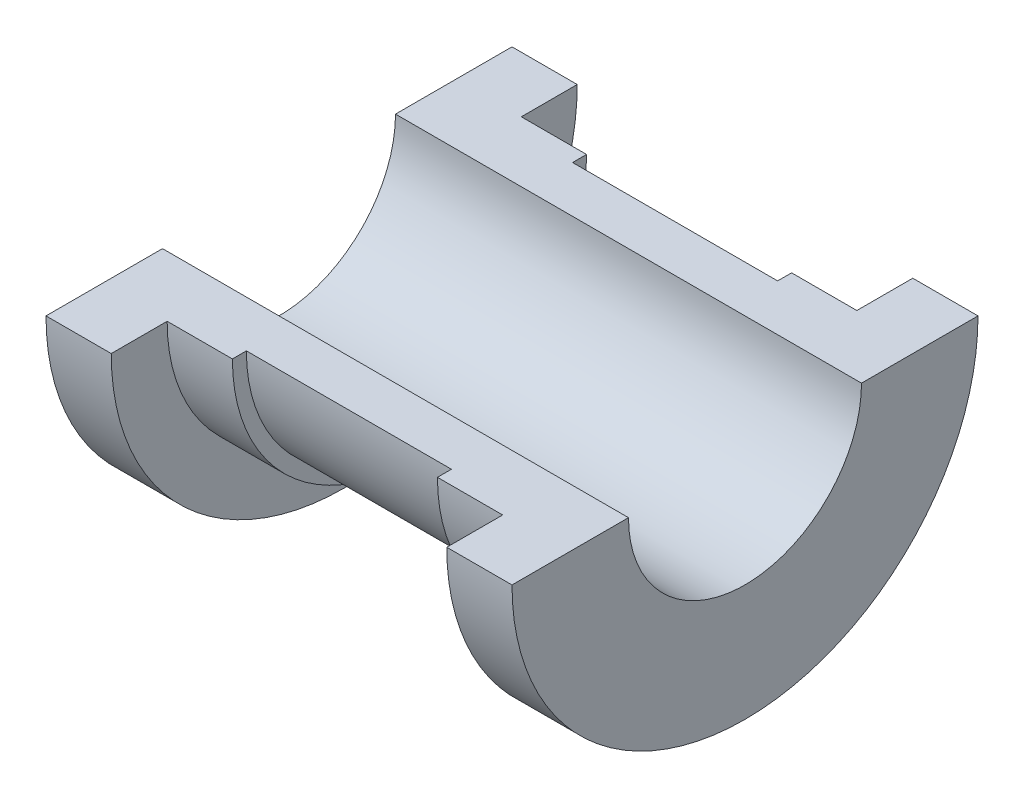
SolidWorks part; units mm, degrees
ref_plane "Front Plane" through (0, 0, 0) normal (0, 0, 1) x (1, 0, 0)
ref_plane "Top Plane" through (0, 0, 0) normal (0, 1, 0) x (1, 0, 0)
ref_plane "Right Plane" through (0, 0, 0) normal (1, 0, 0) x (0, 0, -1)
sketch "Sketch1" plane through (0, 0, 0) normal (0, 0, 1) x (1, 0, 0)
  line L0 (-25, 0) -> (25, 0)
  line L1 (25, 0) -> (25, 25)
  line L2 (25, 25) -> (18, 25)
  line L3 (18, 25) -> (18, 19)
  line L4 (18, 19) -> (11, 19)
  line L5 (11, 19) -> (11, 17.5)
  line L6 (11, 17.5) -> (-11, 17.5)
  line L8 (-11, 19) -> (-11, 17.5)
  line L9 (-18, 19) -> (-11, 19)
  line L10 (-18, 25) -> (-18, 19)
  line L11 (-25, 25) -> (-18, 25)
  line L12 (-25, 0) -> (-25, 25)
  dimension "D2" = 25
  dimension "D4" = 1.5
  dimension "D5" = 6
  dimension "D7" = 7
  dimension "D8" = 7
revolve "Revolve1" add sketch "Sketch1" angle 360 about L0
sketch "Sketch2" plane through (25, 0, 0) normal (1, 0, 0) x (0, 0, -1)
  circle A0 centre (0, 0) radius 12.5
extrude "Cut-Extrude1" cut sketch "Sketch2" against normal through all
sketch "Sketch3" plane through (25, 0, 0) normal (1, 0, 0) x (0, 0, -1)
  line L0 (-25, 0) -> (25, 0)
  circle A0 centre (0, 0) radius 25 construction
extrude "Cut-Extrude4" cut sketch "Sketch3" against normal through all and the other way through all
ref_plane "Plane2" through (0, -17.5, 0) normal (0, 1, 0) x (1, 0, 0)
sketch "Sketch5" plane through (0, -17.5, 0) normal (0, 1, 0) x (1, 0, 0)
  circle A0 centre (0, 0) radius 3
extrude "Boss-Extrude1" add sketch "Sketch5" along normal mid plane 5
